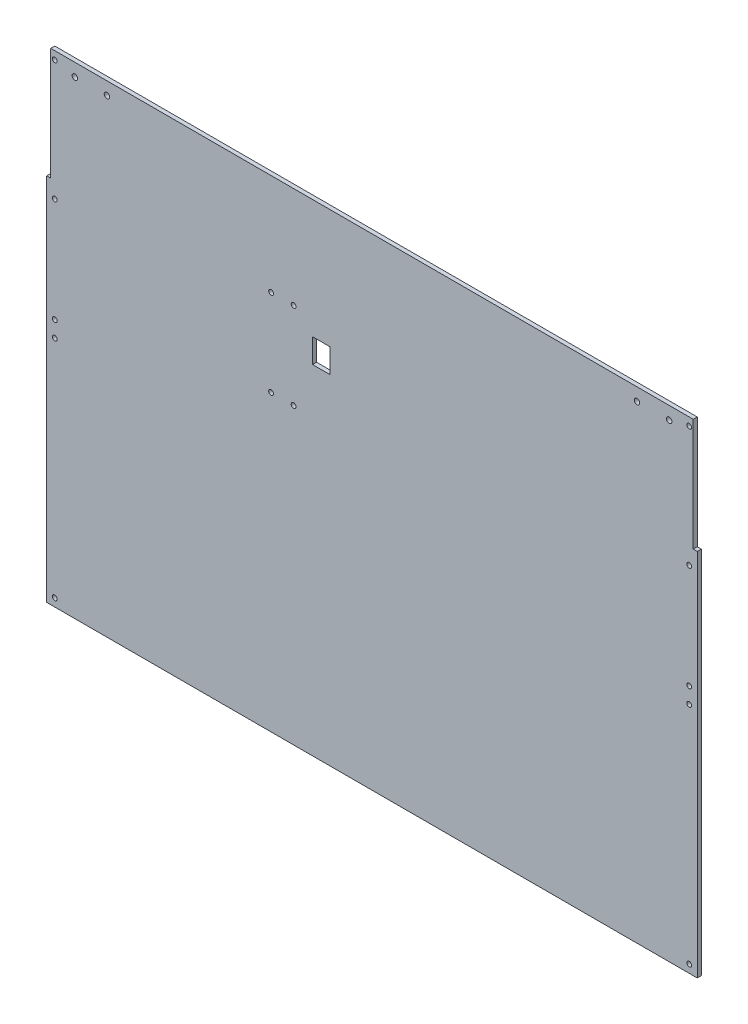
SolidWorks part; units mm, degrees
ref_plane "Front Plane" through (0, 0, 0) normal (0, 0, 1) x (1, 0, 0)
ref_plane "Top Plane" through (0, 0, 0) normal (0, 1, 0) x (1, 0, 0)
ref_plane "Right Plane" through (0, 0, 0) normal (1, 0, 0) x (0, 0, -1)
sketch "Sketch1" plane through (0, 0, 0) normal (0, 0, 1) x (1, 0, 0)
  line L1 (-254, -190.5) -> (254, -190.5)
  line L2 (-254, -190.5) -> (-254, 190.5)
  line L3 (-254, 190.5) -> (254, 190.5)
  line L4 (254, -190.5) -> (254, 190.5)
  line L5 (-254, -190.5) -> (254, 190.5) construction
  line L6 (-254, 190.5) -> (254, -190.5) construction
  point P0 (0, 0)
  dimension "D1" = 508
  dimension "D2" = 381
extrude "Boss-Extrude1" add sketch "Sketch1" along normal blind 3.175
sketch "Sketch3" plane through (0, 0, 3.175) normal (0, 0, 1) x (1, 0, 0)
  line L0 (-254, 190.5) -> (-254, -190.5) construction
  line L1 (-46.99, 77.47) -> (-33.02, 77.47)
  line L2 (-46.99, 77.47) -> (-46.99, 96.52)
  line L3 (-46.99, 96.52) -> (-33.02, 96.52)
  line L4 (-33.02, 77.47) -> (-33.02, 96.52)
  line L5 (254, 190.5) -> (-254, 190.5) construction
  dimension "D1" = 207.01
  dimension "D2" = 13.97
  dimension "D3" = 113.03
  dimension "D4" = 19.05
extrude "Cut-Extrude2" cut sketch "Sketch3" against normal up to surface (3.175 mm away) up to face at (0, 0, 0)
sketch "Sketch2" plane through (0, 0, 3.175) normal (0, 0, 1) x (1, 0, 0)
  line L1 (254, 190.5) -> (-254, 190.5) construction
  line L2 (-254, -190.5) -> (254, -190.5) construction
  line L3 (250.825, 190.5) -> (250.825, -190.5) construction
  line L4 (254, -190.5) -> (254, 190.5) construction
  line L6 (0, 0) -> (0, -50000) construction
  line L8 (-33.02, 96.52) -> (-46.99, 96.52) construction
  line L10 (254, 190.5) -> (-254, 190.5) construction
  circle A2 centre (250.825, 184.15) radius 1.905
  circle A3 centre (250.825, -184.15) radius 1.905
  circle A12 centre (-79.7747, 110.49) radius 1.905
  circle A13 centre (-79.7747, 41.91) radius 1.905
  circle A14 centre (-61.9947, 110.49) radius 1.905
  circle A15 centre (-61.9947, 41.91) radius 1.905
  circle A16 centre (-250.825, 184.15) radius 1.905
  circle A17 centre (-250.825, 88.9) radius 1.905
  circle A18 centre (250.825, 88.9) radius 1.905
  circle A19 centre (250.825, 6.35) radius 1.905
  circle A20 centre (250.825, -6.35) radius 1.905
  circle A21 centre (-250.825, 6.35) radius 1.905
  circle A22 centre (-250.825, -6.35) radius 1.905
  circle A23 centre (-250.825, -184.15) radius 1.905
  point P33 (0, -190.5)
  dimension "D14" = 3.81
  dimension "D12" = 17.78
  dimension "D18" = 3.81
  dimension "D1" = 3.175
  dimension "D5" = 6.35
  dimension "D6" = 6.35
  dimension "D11" = 177.8
  dimension "D13" = 68.58
  dimension "D15" = 15.0047
  dimension "D16" = 13.97
  dimension "D17" = 177.8
  dimension "D19" = 101.6
extrude "Cut-Extrude1" cut sketch "Sketch2" against normal blind 3.175
sketch "Sketch4" plane through (0, 0, 3.175) normal (0, 0, 1) x (1, 0, 0)
  line L0 (254, -190.5) -> (254, 190.5) construction
  line L1 (254, 101.6) -> (257.175, 101.6)
  line L2 (254, 101.6) -> (254, -190.5)
  line L3 (254, -190.5) -> (257.175, -190.5)
  line L4 (257.175, 101.6) -> (257.175, -190.5)
  line L5 (-254, -190.5) -> (254, -190.5) construction
  line L6 (254, 190.5) -> (-254, 190.5) construction
  line L7 (0, 190.5) -> (0, -190.5) construction
  line L8 (-254, -190.5) -> (-257.175, -190.5)
  line L9 (-254, 101.6) -> (-257.175, 101.6)
  line L10 (-254, 101.6) -> (-254, -190.5)
  line L11 (-257.175, 101.6) -> (-257.175, -190.5)
  dimension "D1" = 3.175
  dimension "D2" = 88.9
extrude "Boss-Extrude2" add sketch "Sketch4" against normal blind 3.175
sketch "Sketch5" plane through (0, 0, 0) normal (0, 0, -1) x (-1, 0, 0)
  line L0 (254, 190.5) -> (254, 101.6) construction
  line L1 (-254, 190.5) -> (254, 190.5) construction
  line L2 (-254, 101.6) -> (-254, 190.5) construction
  circle A0 centre (234.95, 180.34) radius 2.159
  circle A1 centre (209.55, 180.34) radius 2.159
  circle A2 centre (-234.95, 180.34) radius 2.159
  circle A3 centre (-209.55, 180.34) radius 2.159
  point P8 (0, 0)
  dimension "D3" = 4.318
  dimension "D1" = 19.05
  dimension "D2" = 44.45
  dimension "D4" = 10.16
  dimension "D5" = 19.05
  dimension "D6" = 44.45
extrude "Cut-Extrude3" cut sketch "Sketch5" against normal through all
